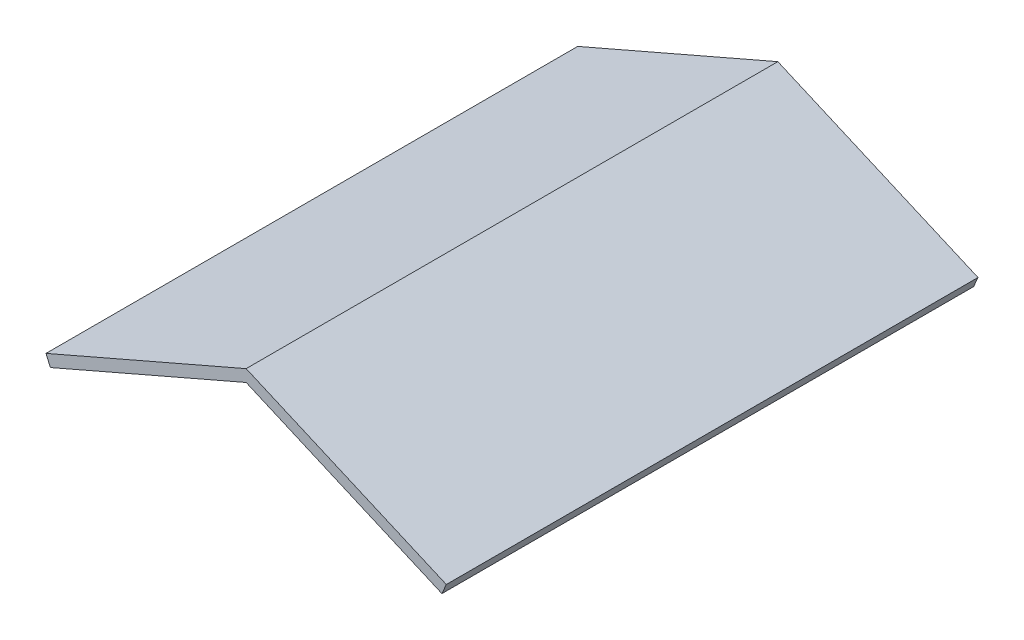
SolidWorks part; units mm, degrees
ref_plane "Спереди" through (0, 0, 0) normal (0, 0, 1) x (1, 0, 0)
ref_plane "Сверху" through (0, 0, 0) normal (0, 1, 0) x (1, 0, 0)
ref_plane "Справа" through (0, 0, 0) normal (1, 0, 0) x (0, 0, -1)
sketch "Эскиз1" plane through (0, 0, 0) normal (0, 0, 1) x (1, 0, 0)
  line L0 (0, 0) -> (0, 3000) construction
  line L1 (0, 0) -> (-9677.7416, 0) construction
  line L2 (-9178, 0) -> (-9378, 0) construction
  line L3 (-9405, 0) -> (-9205, 0) construction
  line L4 (-9677.7416, 0) -> (-9677.7416, 3000) construction
  line L5 (-9677.7416, 3000) -> (-4838.8708, 5100) construction
  line L6 (-4838.8708, 5100) -> (0, 3000) construction
  line L7 (0, 3000) -> (-9677.7416, 3000) construction
  line L8 (-4838.8708, 0) -> (-4838.8708, 5100) construction
  line L9 (-10177.7416, 2783.0072) -> (-4838.8708, 5100)
  line L10 (-4838.8708, 5100) -> (500, 2783.0072)
  line L11 (500, 2783.0072) -> (619.4333, 3058.2084)
  line L12 (619.4333, 3058.2084) -> (-4838.8708, 5427.0335)
  line L13 (-4838.8708, 5427.0335) -> (-10297.1749, 3058.2084)
  line L14 (-10297.1749, 3058.2084) -> (-10177.7416, 2783.0072)
  dimension "D1" = 3000
  dimension "D2" = 2100
  dimension "D3" = 500
  dimension "D4" = 500
  dimension "D5" = 300
extrude "Бобышка-Вытянуть1" add sketch "Эскиз1" against normal blind 500 and the other way blind 14000
